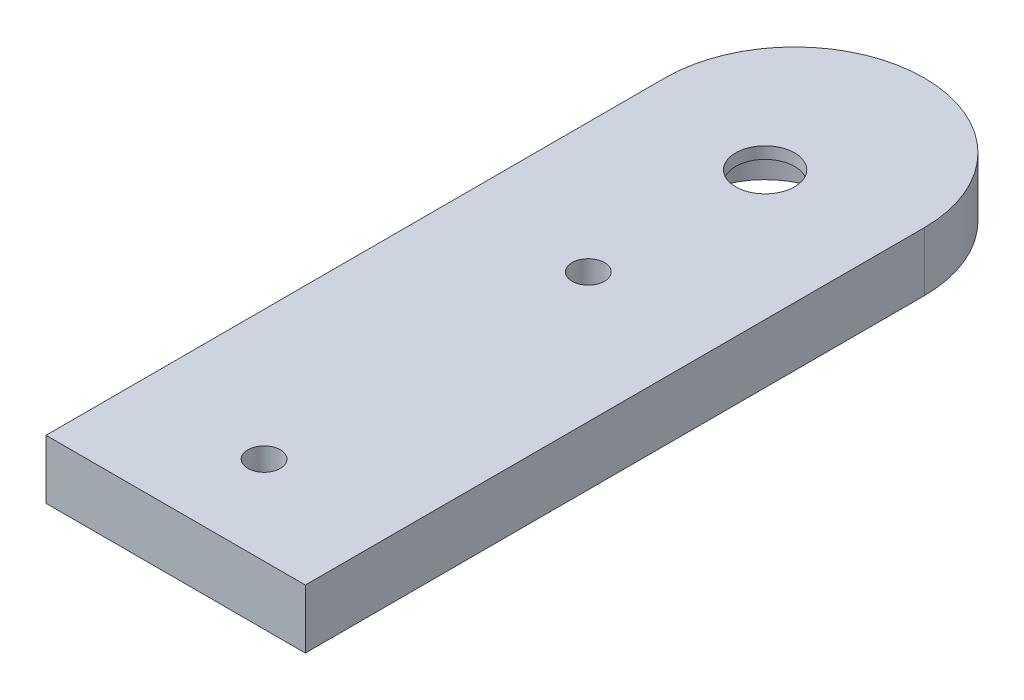
SolidWorks part; units mm, degrees
ref_plane "Front Plane" through (0, 0, 0) normal (0, 0, 1) x (1, 0, 0)
ref_plane "Top Plane" through (0, 0, 0) normal (0, 1, 0) x (1, 0, 0)
ref_plane "Right Plane" through (0, 0, 0) normal (1, 0, 0) x (0, 0, -1)
sketch "Sketch1" plane through (0, 0, 0) normal (0, 1, 0) x (1, 0, 0)
  line L0 (-22, 63.5) -> (-22, 41.5)
  line L1 (-22, -41.5) -> (22, -41.5)
  line L2 (-22, -41.5) -> (-22, 41.5)
  line L4 (22, -41.5) -> (22, 41.5)
  line L5 (22, 63.5) -> (22, 41.5)
  circle A2 centre (0, -26.5) radius 2.75
  circle A6 centre (0, 58.5) radius 12.1
  circle A7 centre (0, 28.5) radius 2.75
  arc A9 (-22, 63.5) -> (22, 63.5) centre (0, 63.5) cw
  point P0 (0, 0)
  dimension "D2" = 5.5
  dimension "D3" = 22
  dimension "D5" = 5.5
  dimension "D6" = 24.2
  dimension "D9" = 41.5
  dimension "D1" = 44
  dimension "D7" = 15
  dimension "D8" = 22
  dimension "D4" = 55
  dimension "D10" = 30
extrude "Boss-Extrude1" add sketch "Sketch1" along normal blind 8
sketch "Sketch2" plane through (0, 8, 0) normal (0, 1, 0) x (1, 0, 0)
  line L0 (-22, -41.5) -> (22, -41.5)
  line L1 (22, -41.5) -> (22, 63.5)
  line L3 (-22, 63.5) -> (-22, -41.5)
  arc A0 (-22, 63.5) -> (22, 63.5) centre (0, 63.5) cw
  circle A1 centre (0, 28.5) radius 2.75
  circle A2 centre (0, -26.5) radius 2.75
  circle A3 centre (0, 58.5) radius 5
  dimension "D1" = 10
extrude "Boss-Extrude2" add sketch "Sketch2" along normal blind 2
